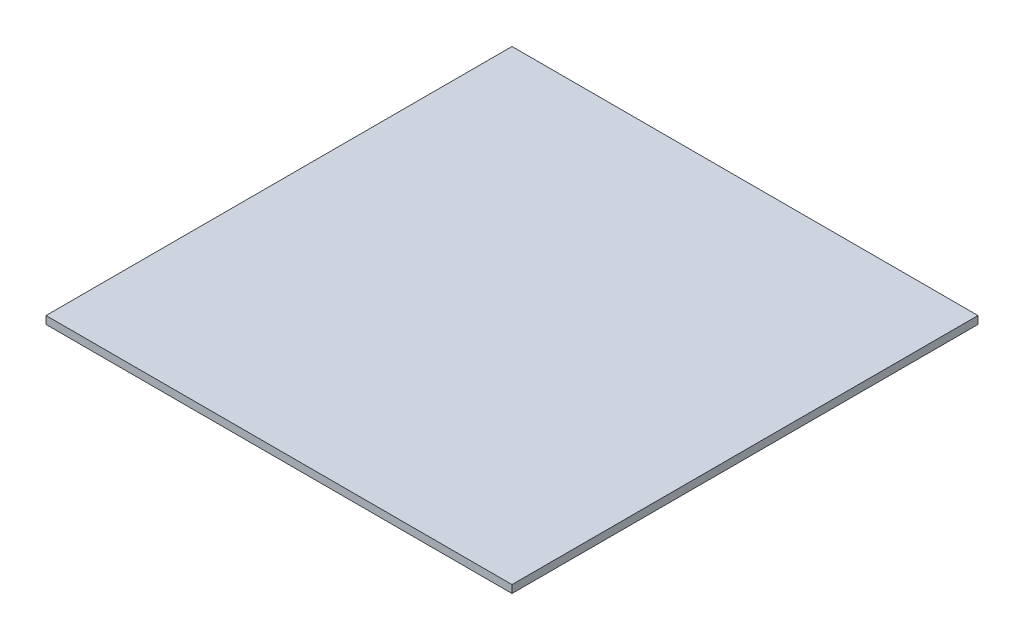
SolidWorks part; units mm, degrees
ref_plane "前视基准面" through (0, 0, 0) normal (0, 0, 1) x (1, 0, 0)
ref_plane "上视基准面" through (0, 0, 0) normal (0, 1, 0) x (1, 0, 0)
ref_plane "右视基准面" through (0, 0, 0) normal (1, 0, 0) x (0, 0, -1)
sketch "草图1" plane through (0, 0, 0) normal (0, 1, 0) x (1, 0, 0)
  line L1 (-300, 300) -> (300, 300)
  line L2 (-300, 300) -> (-300, -300)
  line L3 (-300, -300) -> (300, -300)
  line L4 (300, 300) -> (300, -300)
  line L5 (-300, 300) -> (300, -300) construction
  line L6 (-300, -300) -> (300, 300) construction
  point P0 (0, 0)
  dimension "D1" = 600
  dimension "D2" = 600
extrude "凸台-拉伸1" add sketch "草图1" along normal blind 10
